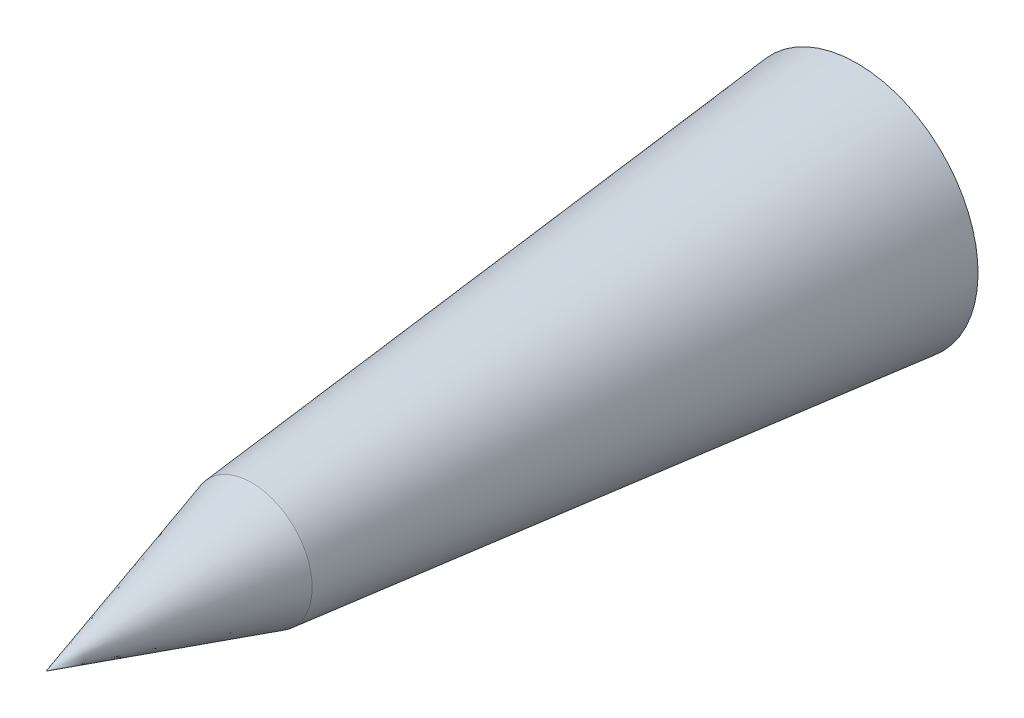
SolidWorks part; units mm, degrees
ref_plane "Front Plane" through (0, 0, 0) normal (0, 0, 1) x (1, 0, 0)
ref_plane "Top Plane" through (0, 0, 0) normal (0, 1, 0) x (1, 0, 0)
ref_plane "Right Plane" through (0, 0, 0) normal (1, 0, 0) x (0, 0, -1)
sketch "Sketch1" plane through (0, 0, 0) normal (1, 0, 0) x (0, 0, -1)
  line L0 (0, 50.8) -> (0, 0)
  line L1 (-254, 25.4) -> (-254, 0) construction
  line L2 (0, 0) -> (-340.285, 0)
  spline S0 degree 1 poles (-279.146, 22.8854) (25.4, 53.34) knots 0 0 1 1 construction
  spline S1 degree 1 poles (-254, 25.4) (0, 50.8) knots 0.082569 0.082569 0.916597 0.916597
  spline S2 degree 1 poles (-348.9135, -2.54) (-245.3715, 27.94) knots 0 0 1 1 construction
  spline S3 degree 1 poles (-340.285, 0) (-254, 25.4) knots 0.083333 0.083333 0.916667 0.916667
  dimension "D1" = 25.4
  dimension "D2" = 50.8
revolve "Revolve1" add sketch "Sketch1" angle 360 about L2
equation "\"L1\"= 10'length 1"
equation "\"L2\"= 6.5'length 2"
equation "\"L\"= \"L1\" + \"L2\"'overall length"
equation "\"R1\"= 1'Radius at length 1"
equation "\"R2\"= 2'Radius at length 2"
equation "\"phi1\"= atn ( \"R1\" / \"L1\" )'half angle 1"
equation "\"phi2\"= atn ( ( \"R2\" - \"R1\" ) / \"L2\" )'half angle 2"
equation "\"D2@Sketch1\"=\"R2\""
equation "\"D1@Sketch1\"=\"R1\""
